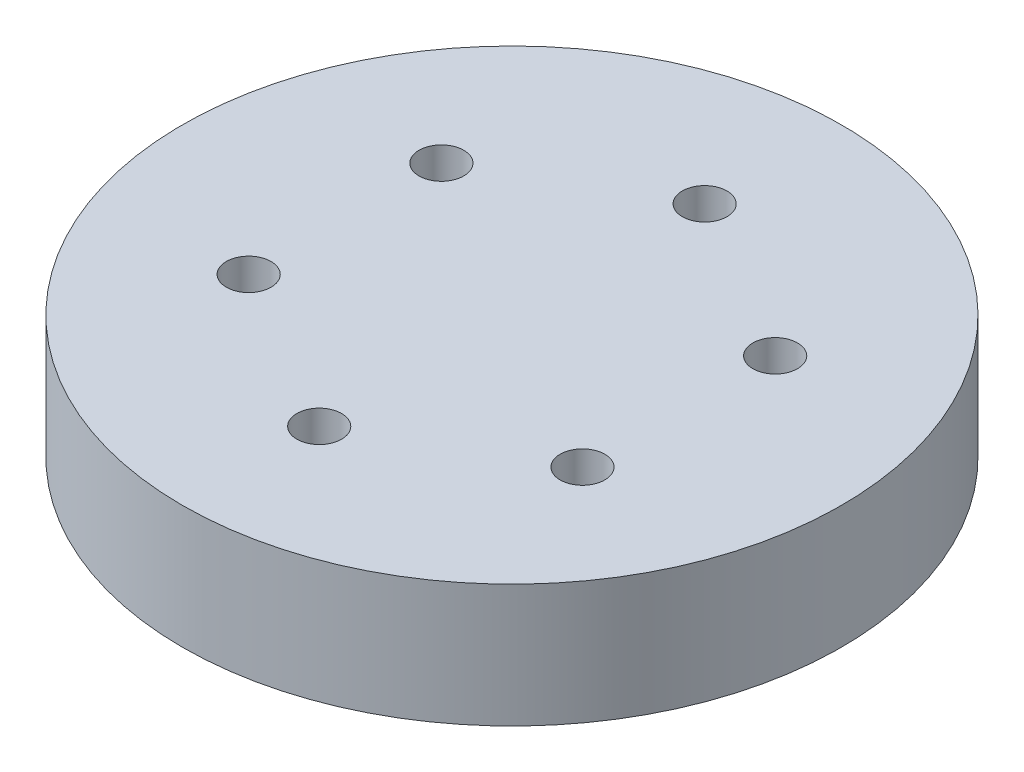
SolidWorks part; units mm, degrees
ref_plane "前视基准面" through (0, 0, 0) normal (0, 0, 1) x (1, 0, 0)
ref_plane "上视基准面" through (0, 0, 0) normal (0, 1, 0) x (1, 0, 0)
ref_plane "右视基准面" through (0, 0, 0) normal (1, 0, 0) x (0, 0, -1)
other "Configuration Table"
sketch "草图1" plane through (0, 0, 0) normal (0, 1, 0) x (1, 0, 0)
  circle A0 centre (0, 0) radius 29.5
  circle A1 centre (0, 17.25) radius 2
  circle A2 centre (0, 0) radius 17.25 construction
  circle A3 centre (14.9389, 8.625) radius 2
  circle A4 centre (14.9389, -8.625) radius 2
  circle A5 centre (0, -17.25) radius 2
  circle A6 centre (-14.9389, -8.625) radius 2
  circle A7 centre (-14.9389, 8.625) radius 2
  point P19 (0, 0)
  dimension "D1" = 59
  dimension "D2" = 34.5
  dimension "D3" = 4
extrude "凸台-拉伸1" add sketch "草图1" along normal blind 11
